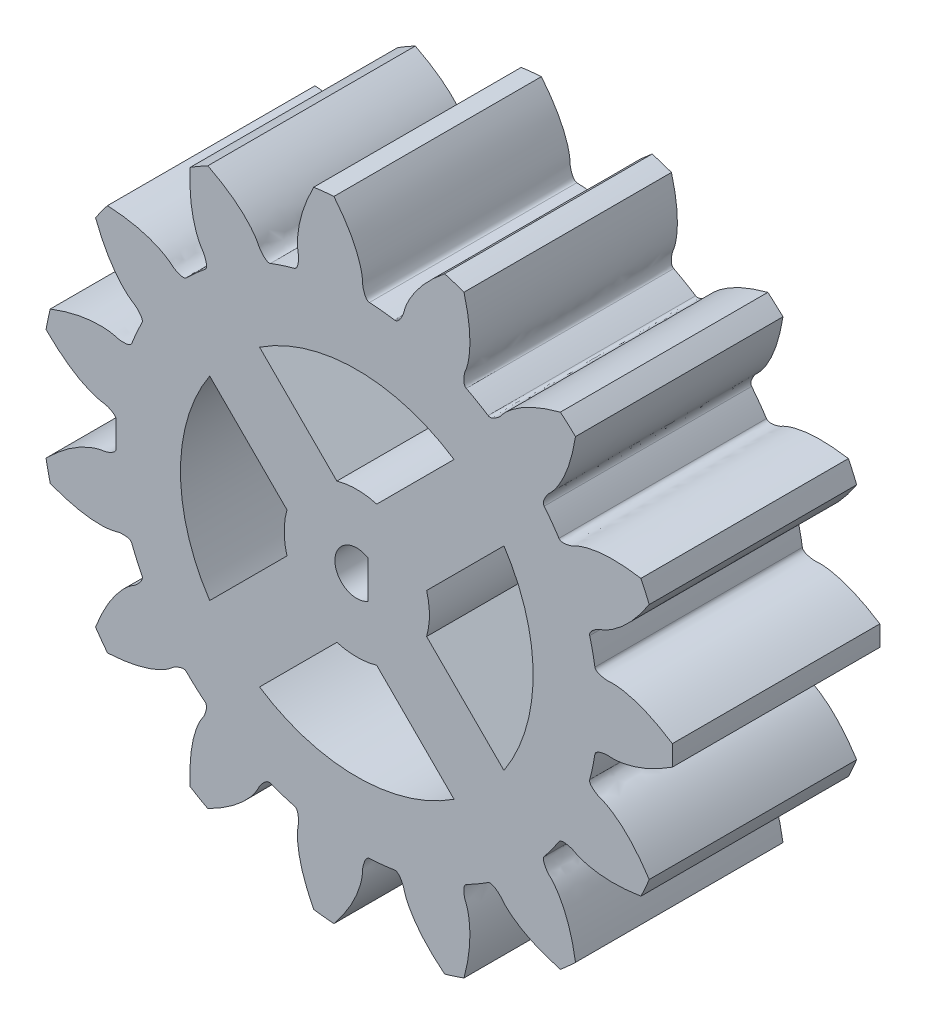
SolidWorks part; units mm, degrees
ref_plane "Front Plane" through (0, 0, 0) normal (0, 0, 1) x (1, 0, 0)
ref_plane "Top Plane" through (0, 0, 0) normal (0, 1, 0) x (1, 0, 0)
ref_plane "Right Plane" through (0, 0, 0) normal (1, 0, 0) x (0, 0, -1)
sketch "Model" plane through (0, 0, 0) normal (0, 0, 1) x (1, 0, 0)
  line L0 (451.3212, 9.2467) -> (451.0258, 8.0362)
  line L1 (451.0258, 8.0362) -> (450.8033, 6.8101)
  line L2 (450.8033, 6.8101) -> (450.8481, 6.7622)
  line L3 (450.8481, 6.7622) -> (451.5704, 6.0588)
  line L4 (451.5704, 6.0588) -> (452.2736, 5.4349)
  line L5 (452.2736, 5.4349) -> (452.9522, 4.8871)
  line L6 (452.9522, 4.8871) -> (453.6007, 4.4118)
  line L7 (453.6007, 4.4118) -> (454.2138, 4.0048)
  line L8 (454.2138, 4.0048) -> (454.7869, 3.6617)
  line L9 (454.7869, 3.6617) -> (455.3153, 3.3779)
  line L10 (455.3153, 3.3779) -> (455.7949, 3.1483)
  line L11 (455.7949, 3.1483) -> (456.222, 2.9678)
  line L12 (456.222, 2.9678) -> (456.5932, 2.8309)
  line L13 (456.5932, 2.8309) -> (456.9055, 2.732)
  line L14 (456.9055, 2.732) -> (457.1563, 2.6652)
  line L15 (457.1563, 2.6652) -> (457.3434, 2.6246)
  line L16 (457.3434, 2.6246) -> (457.9089, 2.5292)
  line L17 (457.9089, 2.5292) -> (458.3538, 2.4053)
  line L18 (458.3538, 2.4053) -> (458.7196, 2.2489)
  line L19 (458.7196, 2.2489) -> (459.0044, 2.0671)
  line L20 (459.0044, 2.0671) -> (459.2067, 1.8671)
  line L21 (459.2067, 1.8671) -> (459.3257, 1.6561)
  line L22 (459.3257, 1.6561) -> (459.3608, 1.4416)
  line L23 (459.3608, 1.4416) -> (459.3257, 0.6868)
  line L24 (459.3257, 0.6868) -> (459.3257, -0.6868)
  line L25 (459.3257, -0.6868) -> (459.3608, -1.4416)
  line L26 (459.3608, -1.4416) -> (459.3257, -1.6561)
  line L27 (459.3257, -1.6561) -> (459.2067, -1.8671)
  line L28 (459.2067, -1.8671) -> (459.0044, -2.0671)
  line L29 (459.0044, -2.0671) -> (458.7196, -2.2489)
  line L30 (458.7196, -2.2489) -> (458.3538, -2.4053)
  line L31 (458.3538, -2.4053) -> (457.9089, -2.5292)
  line L32 (457.9089, -2.5292) -> (457.3434, -2.6246)
  line L33 (457.3434, -2.6246) -> (457.1563, -2.6652)
  line L34 (457.1563, -2.6652) -> (456.9055, -2.732)
  line L35 (456.9055, -2.732) -> (456.5932, -2.8309)
  line L36 (456.5932, -2.8309) -> (456.222, -2.9678)
  line L37 (456.222, -2.9678) -> (455.7949, -3.1483)
  line L38 (455.7949, -3.1483) -> (455.3153, -3.3779)
  line L39 (455.3153, -3.3779) -> (454.7869, -3.6617)
  line L40 (454.7869, -3.6617) -> (454.2138, -4.0048)
  line L41 (454.2138, -4.0048) -> (453.6007, -4.4118)
  line L42 (453.6007, -4.4118) -> (452.9522, -4.8871)
  line L43 (452.9522, -4.8871) -> (452.2736, -5.4349)
  line L44 (452.2736, -5.4349) -> (451.5704, -6.0588)
  line L45 (451.5704, -6.0588) -> (450.8481, -6.7622)
  line L46 (450.8481, -6.7622) -> (450.8033, -6.8101)
  line L47 (450.8033, -6.8101) -> (451.0258, -8.0362)
  line L48 (451.0258, -8.0362) -> (451.3212, -9.2467)
  line L49 (451.3212, -9.2467) -> (451.3817, -9.2723)
  line L50 (451.3817, -9.2723) -> (452.3276, -9.6211)
  line L51 (452.3276, -9.6211) -> (453.2238, -9.905)
  line L52 (453.2238, -9.905) -> (454.0665, -10.1294)
  line L53 (454.0665, -10.1294) -> (454.8522, -10.2999)
  line L54 (454.8522, -10.2999) -> (455.5779, -10.4224)
  line L55 (455.5779, -10.4224) -> (456.2409, -10.5027)
  line L56 (456.2409, -10.5027) -> (456.8391, -10.5471)
  line L57 (456.8391, -10.5471) -> (457.3707, -10.5617)
  line L58 (457.3707, -10.5617) -> (457.8343, -10.5529)
  line L59 (457.8343, -10.5529) -> (458.2291, -10.527)
  line L60 (458.2291, -10.527) -> (458.5546, -10.4903)
  line L61 (458.5546, -10.4903) -> (458.8109, -10.4493)
  line L62 (458.8109, -10.4493) -> (458.9983, -10.4103)
  line L63 (458.9983, -10.4103) -> (459.5537, -10.2675)
  line L64 (459.5537, -10.2675) -> (460.0105, -10.1996)
  line L65 (460.0105, -10.1996) -> (460.4084, -10.1937)
  line L66 (460.4084, -10.1937) -> (460.7425, -10.244)
  line L67 (460.7425, -10.244) -> (461.0087, -10.3444)
  line L68 (461.0087, -10.3444) -> (461.2031, -10.4888)
  line L69 (461.2031, -10.4888) -> (461.3225, -10.6705)
  line L70 (461.3225, -10.6705) -> (461.5974, -11.3743)
  line L71 (461.5974, -11.3743) -> (462.1561, -12.6291)
  line L72 (462.1561, -12.6291) -> (462.4952, -13.3044)
  line L73 (462.4952, -13.3044) -> (462.5503, -13.5147)
  line L74 (462.5503, -13.5147) -> (462.5275, -13.7558)
  line L75 (462.5275, -13.7558) -> (462.424, -14.0208)
  line L76 (462.424, -14.0208) -> (462.2378, -14.3027)
  line L77 (462.2378, -14.3027) -> (461.9672, -14.5944)
  line L78 (461.9672, -14.5944) -> (461.6111, -14.8885)
  line L79 (461.6111, -14.8885) -> (461.1333, -15.2057)
  line L80 (461.1333, -15.2057) -> (460.9789, -15.3189)
  line L81 (460.9789, -15.3189) -> (460.777, -15.4819)
  line L82 (460.777, -15.4819) -> (460.5319, -15.6993)
  line L83 (460.5319, -15.6993) -> (460.2485, -15.9753)
  line L84 (460.2485, -15.9753) -> (459.9317, -16.3139)
  line L85 (459.9317, -16.3139) -> (459.5869, -16.7187)
  line L86 (459.5869, -16.7187) -> (459.2196, -17.193)
  line L87 (459.2196, -17.193) -> (458.8357, -17.7395)
  line L88 (458.8357, -17.7395) -> (458.4411, -18.3607)
  line L89 (458.4411, -18.3607) -> (458.0421, -19.0587)
  line L90 (458.0421, -19.0587) -> (457.6449, -19.8351)
  line L91 (457.6449, -19.8351) -> (457.2562, -20.6911)
  line L92 (457.2562, -20.6911) -> (456.8825, -21.6274)
  line L93 (456.8825, -21.6274) -> (456.861, -21.6895)
  line L94 (456.861, -21.6895) -> (457.563, -22.719)
  line L95 (457.563, -22.719) -> (458.3252, -23.7048)
  line L96 (458.3252, -23.7048) -> (458.3909, -23.7035)
  line L97 (458.3909, -23.7035) -> (459.3969, -23.6375)
  line L98 (459.3969, -23.6375) -> (460.3311, -23.5323)
  line L99 (460.3311, -23.5323) -> (461.1922, -23.3945)
  line L100 (461.1922, -23.3945) -> (461.9794, -23.2307)
  line L101 (461.9794, -23.2307) -> (462.6921, -23.0474)
  line L102 (462.6921, -23.0474) -> (463.3305, -22.8511)
  line L103 (463.3305, -22.8511) -> (463.895, -22.6483)
  line L104 (463.895, -22.6483) -> (464.3866, -22.4455)
  line L105 (464.3866, -22.4455) -> (464.8065, -22.2489)
  line L106 (464.8065, -22.2489) -> (465.1566, -22.0646)
  line L107 (465.1566, -22.0646) -> (465.4391, -21.8987)
  line L108 (465.4391, -21.8987) -> (465.6565, -21.757)
  line L109 (465.6565, -21.757) -> (465.8119, -21.6452)
  line L110 (465.8119, -21.6452) -> (466.2612, -21.2888)
  line L111 (466.2612, -21.2888) -> (466.6509, -21.041)
  line L112 (466.6509, -21.041) -> (467.012, -20.8738)
  line L113 (467.012, -20.8738) -> (467.3376, -20.7838)
  line L114 (467.3376, -20.7838) -> (467.6217, -20.7673)
  line L115 (467.6217, -20.7673) -> (467.858, -20.8201)
  line L116 (467.858, -20.8201) -> (468.041, -20.9375)
  line L117 (468.041, -20.9375) -> (468.5784, -21.4687)
  line L118 (468.5784, -21.4687) -> (469.5992, -22.3878)
  line L119 (469.5992, -22.3878) -> (470.1836, -22.8667)
  line L120 (470.1836, -22.8667) -> (470.3195, -23.0364)
  line L121 (470.3195, -23.0364) -> (470.3967, -23.2659)
  line L122 (470.3967, -23.2659) -> (470.41, -23.5501)
  line L123 (470.41, -23.5501) -> (470.3545, -23.8834)
  line L124 (470.3545, -23.8834) -> (470.226, -24.26)
  line L125 (470.226, -24.26) -> (470.0203, -24.6735)
  line L126 (470.0203, -24.6735) -> (469.7128, -25.1576)
  line L127 (469.7128, -25.1576) -> (469.6178, -25.3238)
  line L128 (469.6178, -25.3238) -> (469.4996, -25.5548)
  line L129 (469.4996, -25.5548) -> (469.3642, -25.8531)
  line L130 (469.3642, -25.8531) -> (469.2175, -26.2205)
  line L131 (469.2175, -26.2205) -> (469.0659, -26.6587)
  line L132 (469.0659, -26.6587) -> (468.9155, -27.1688)
  line L133 (468.9155, -27.1688) -> (468.7729, -27.7514)
  line L134 (468.7729, -27.7514) -> (468.6444, -28.4068)
  line L135 (468.6444, -28.4068) -> (468.5366, -29.1348)
  line L136 (468.5366, -29.1348) -> (468.4559, -29.9348)
  line L137 (468.4559, -29.9348) -> (468.4089, -30.8056)
  line L138 (468.4089, -30.8056) -> (468.402, -31.7457)
  line L139 (468.402, -31.7457) -> (468.4414, -32.7531)
  line L140 (468.4414, -32.7531) -> (468.4471, -32.8185)
  line L141 (468.4471, -32.8185) -> (469.5071, -33.4735)
  line L142 (469.5071, -33.4735) -> (470.6044, -34.064)
  line L143 (470.6044, -34.064) -> (470.6638, -34.0362)
  line L144 (470.6638, -34.0362) -> (471.556, -33.5666)
  line L145 (471.556, -33.5666) -> (472.3667, -33.0906)
  line L146 (472.3667, -33.0906) -> (473.0973, -32.6145)
  line L147 (473.0973, -32.6145) -> (473.7498, -32.1447)
  line L148 (473.7498, -32.1447) -> (474.3263, -31.6873)
  line L149 (474.3263, -31.6873) -> (474.8297, -31.2483)
  line L150 (474.8297, -31.2483) -> (475.2629, -30.8335)
  line L151 (475.2629, -30.8335) -> (475.6295, -30.4483)
  line L152 (475.6295, -30.4483) -> (475.9332, -30.0978)
  line L153 (475.9332, -30.0978) -> (476.1781, -29.7871)
  line L154 (476.1781, -29.7871) -> (476.3686, -29.5207)
  line L155 (476.3686, -29.5207) -> (476.5096, -29.3028)
  line L156 (476.5096, -29.3028) -> (476.6061, -29.1374)
  line L157 (476.6061, -29.1374) -> (476.8715, -28.6291)
  line L158 (476.8715, -28.6291) -> (477.1268, -28.2442)
  line L159 (477.1268, -28.2442) -> (477.3886, -27.9446)
  line L160 (477.3886, -27.9446) -> (477.6496, -27.7299)
  line L161 (477.6496, -27.7299) -> (477.9023, -27.5993)
  line L162 (477.9023, -27.5993) -> (478.1397, -27.5514)
  line L163 (478.1397, -27.5514) -> (478.3546, -27.5842)
  line L164 (478.3546, -27.5842) -> (479.0616, -27.8509)
  line L165 (479.0616, -27.8509) -> (480.3679, -28.2754)
  line L166 (480.3679, -28.2754) -> (481.0967, -28.4752)
  line L167 (481.0967, -28.4752) -> (481.2898, -28.5749)
  line L168 (481.2898, -28.5749) -> (481.4537, -28.7532)
  line L169 (481.4537, -28.7532) -> (481.5814, -29.0075)
  line L170 (481.5814, -29.0075) -> (481.6663, -29.3345)
  line L171 (481.6663, -29.3345) -> (481.7021, -29.7308)
  line L172 (481.7021, -29.7308) -> (481.6823, -30.1922)
  line L173 (481.6823, -30.1922) -> (481.5983, -30.7595)
  line L174 (481.5983, -30.7595) -> (481.5791, -30.95)
  line L175 (481.5791, -30.95) -> (481.5651, -31.2091)
  line L176 (481.5651, -31.2091) -> (481.5627, -31.5367)
  line L177 (481.5627, -31.5367) -> (481.5782, -31.932)
  line L178 (481.5782, -31.932) -> (481.6179, -32.394)
  line L179 (481.6179, -32.394) -> (481.688, -32.9211)
  line L180 (481.688, -32.9211) -> (481.7947, -33.5114)
  line L181 (481.7947, -33.5114) -> (481.9439, -34.1624)
  line L182 (481.9439, -34.1624) -> (482.1415, -34.8713)
  line L183 (482.1415, -34.8713) -> (482.3932, -35.6349)
  line L184 (482.3932, -35.6349) -> (482.7044, -36.4495)
  line L185 (482.7044, -36.4495) -> (483.0805, -37.3112)
  line L186 (483.0805, -37.3112) -> (483.5263, -38.2154)
  line L187 (483.5263, -38.2154) -> (483.558, -38.2729)
  line L188 (483.558, -38.2729) -> (484.7928, -38.4402)
  line L189 (484.7928, -38.4402) -> (486.0354, -38.5333)
  line L190 (486.0354, -38.5333) -> (486.0784, -38.4837)
  line L191 (486.0784, -38.4837) -> (486.7025, -37.6919)
  line L192 (486.7025, -37.6919) -> (487.2494, -36.9272)
  line L193 (487.2494, -36.9272) -> (487.7232, -36.1951)
  line L194 (487.7232, -36.1951) -> (488.1282, -35.5005)
  line L195 (488.1282, -35.5005) -> (488.4689, -34.8482)
  line L196 (488.4689, -34.8482) -> (488.7502, -34.2424)
  line L197 (488.7502, -34.2424) -> (488.9772, -33.6872)
  line L198 (488.9772, -33.6872) -> (489.1554, -33.1862)
  line L199 (489.1554, -33.1862) -> (489.2903, -32.7426)
  line L200 (489.2903, -32.7426) -> (489.3876, -32.3591)
  line L201 (489.3876, -32.3591) -> (489.4534, -32.0382)
  line L202 (489.4534, -32.0382) -> (489.4936, -31.7818)
  line L203 (489.4936, -31.7818) -> (489.5144, -31.5915)
  line L204 (489.5144, -31.5915) -> (489.5502, -31.0192)
  line L205 (489.5502, -31.0192) -> (489.6268, -30.5637)
  line L206 (489.6268, -30.5637) -> (489.7441, -30.1835)
  line L207 (489.7441, -30.1835) -> (489.8952, -29.8813)
  line L208 (489.8952, -29.8813) -> (490.073, -29.6592)
  line L209 (490.073, -29.6592) -> (490.2704, -29.5188)
  line L210 (490.2704, -29.5188) -> (490.48, -29.4614)
  line L211 (490.48, -29.4614) -> (491.2344, -29.4175)
  line L212 (491.2344, -29.4175) -> (492.6004, -29.2739)
  line L213 (492.6004, -29.2739) -> (493.3474, -29.1601)
  line L214 (493.3474, -29.1601) -> (493.5644, -29.1726)
  line L215 (493.5644, -29.1726) -> (493.7867, -29.2688)
  line L216 (493.7867, -29.2688) -> (494.0068, -29.4491)
  line L217 (494.0068, -29.4491) -> (494.2174, -29.7134)
  line L218 (494.2174, -29.7134) -> (494.4111, -30.0608)
  line L219 (494.4111, -30.0608) -> (494.5808, -30.4904)
  line L220 (494.5808, -30.4904) -> (494.7348, -31.0428)
  line L221 (494.7348, -31.0428) -> (494.7948, -31.2246)
  line L222 (494.7948, -31.2246) -> (494.8874, -31.4671)
  line L223 (494.8874, -31.4671) -> (495.0184, -31.7673)
  line L224 (495.0184, -31.7673) -> (495.1933, -32.1221)
  line L225 (495.1933, -32.1221) -> (495.4175, -32.5281)
  line L226 (495.4175, -32.5281) -> (495.696, -32.9811)
  line L227 (495.696, -32.9811) -> (496.0335, -33.4769)
  line L228 (496.0335, -33.4769) -> (496.4346, -34.011)
  line L229 (496.4346, -34.011) -> (496.9035, -34.5782)
  line L230 (496.9035, -34.5782) -> (497.444, -35.1734)
  line L231 (497.444, -35.1734) -> (498.0596, -35.791)
  line L232 (498.0596, -35.791) -> (498.7536, -36.4252)
  line L233 (498.7536, -36.4252) -> (499.5287, -37.07)
  line L234 (499.5287, -37.07) -> (499.581, -37.1096)
  line L235 (499.581, -37.1096) -> (500.7771, -36.7602)
  line L236 (500.7771, -36.7602) -> (501.9502, -36.3398)
  line L237 (501.9502, -36.3398) -> (501.9693, -36.277)
  line L238 (501.9693, -36.277) -> (502.2173, -35.2998)
  line L239 (502.2173, -35.2998) -> (502.406, -34.3788)
  line L240 (502.406, -34.3788) -> (502.5411, -33.5173)
  line L241 (502.5411, -33.5173) -> (502.6285, -32.718)
  line L242 (502.6285, -32.718) -> (502.6744, -31.9835)
  line L243 (502.6744, -31.9835) -> (502.685, -31.3157)
  line L244 (502.685, -31.3157) -> (502.6666, -30.7162)
  line L245 (502.6666, -30.7162) -> (502.6256, -30.186)
  line L246 (502.6256, -30.186) -> (502.5684, -29.7258)
  line L247 (502.5684, -29.7258) -> (502.5013, -29.3359)
  line L248 (502.5013, -29.3359) -> (502.4308, -29.016)
  line L249 (502.4308, -29.016) -> (502.3633, -28.7655)
  line L250 (502.3633, -28.7655) -> (502.3049, -28.5831)
  line L251 (502.3049, -28.5831) -> (502.1048, -28.0457)
  line L252 (502.1048, -28.0457) -> (501.9896, -27.5984)
  line L253 (501.9896, -27.5984) -> (501.9421, -27.2034)
  line L254 (501.9421, -27.2034) -> (501.9572, -26.8659)
  line L255 (501.9572, -26.8659) -> (502.0293, -26.5907)
  line L256 (502.0293, -26.5907) -> (502.1525, -26.3822)
  line L257 (502.1525, -26.3822) -> (502.3207, -26.2445)
  line L258 (502.3207, -26.2445) -> (502.9919, -25.8975)
  line L259 (502.9919, -25.8975) -> (504.1815, -25.2107)
  line L260 (504.1815, -25.2107) -> (504.8176, -24.8029)
  line L261 (504.8176, -24.8029) -> (505.021, -24.7261)
  line L262 (505.021, -24.7261) -> (505.2631, -24.7236)
  line L263 (505.2631, -24.7236) -> (505.5375, -24.7988)
  line L264 (505.5375, -24.7988) -> (505.8374, -24.9545)
  line L265 (505.8374, -24.9545) -> (506.1557, -25.1931)
  line L266 (506.1557, -25.1931) -> (506.4855, -25.5165)
  line L267 (506.4855, -25.5165) -> (506.8508, -25.9585)
  line L268 (506.8508, -25.9585) -> (506.9795, -26.1003)
  line L269 (506.9795, -26.1003) -> (507.1628, -26.2841)
  line L270 (507.1628, -26.2841) -> (507.4046, -26.505)
  line L271 (507.4046, -26.505) -> (507.7087, -26.7581)
  line L272 (507.7087, -26.7581) -> (508.0786, -27.0377)
  line L273 (508.0786, -27.0377) -> (508.5172, -27.3383)
  line L274 (508.5172, -27.3383) -> (509.0273, -27.654)
  line L275 (509.0273, -27.654) -> (509.6109, -27.9787)
  line L276 (509.6109, -27.9787) -> (510.27, -28.3062)
  line L277 (510.27, -28.3062) -> (511.0058, -28.6301)
  line L278 (511.0058, -28.6301) -> (511.8195, -28.9439)
  line L279 (511.8195, -28.9439) -> (512.7114, -29.241)
  line L280 (512.7114, -29.241) -> (513.6817, -29.5148)
  line L281 (513.6817, -29.5148) -> (513.7457, -29.5297)
  line L282 (513.7457, -29.5297) -> (514.6962, -28.724)
  line L283 (514.6962, -28.724) -> (515.5969, -27.8628)
  line L284 (515.5969, -27.8628) -> (515.5888, -27.7977)
  line L285 (515.5888, -27.7977) -> (515.4179, -26.8041)
  line L286 (515.4179, -26.8041) -> (515.2157, -25.886)
  line L287 (515.2157, -25.886) -> (514.9886, -25.044)
  line L288 (514.9886, -25.044) -> (514.7434, -24.2783)
  line L289 (514.7434, -24.2783) -> (514.4866, -23.5886)
  line L290 (514.4866, -23.5886) -> (514.2247, -22.9742)
  line L291 (514.2247, -22.9742) -> (513.964, -22.434)
  line L292 (513.964, -22.434) -> (513.7109, -21.9663)
  line L293 (513.7109, -21.9663) -> (513.4715, -21.5693)
  line L294 (513.4715, -21.5693) -> (513.2516, -21.2403)
  line L295 (513.2516, -21.2403) -> (513.0571, -20.9767)
  line L296 (513.0571, -20.9767) -> (512.8935, -20.7753)
  line L297 (512.8935, -20.7753) -> (512.766, -20.6325)
  line L298 (512.766, -20.6325) -> (512.3646, -20.2229)
  line L299 (512.3646, -20.2229) -> (512.0774, -19.8612)
  line L300 (512.0774, -19.8612) -> (511.8734, -19.5196)
  line L301 (511.8734, -19.5196) -> (511.7499, -19.2051)
  line L302 (511.7499, -19.2051) -> (511.7038, -18.9244)
  line L303 (511.7038, -18.9244) -> (511.7315, -18.6838)
  line L304 (511.7315, -18.6838) -> (511.8292, -18.4896)
  line L305 (511.8292, -18.4896) -> (512.3013, -17.8996)
  line L306 (512.3013, -17.8996) -> (513.1087, -16.7884)
  line L307 (513.1087, -16.7884) -> (513.5239, -16.1571)
  line L308 (513.5239, -16.1571) -> (513.6784, -16.0042)
  line L309 (513.6784, -16.0042) -> (513.8987, -15.9034)
  line L310 (513.8987, -15.9034) -> (514.1799, -15.8605)
  line L311 (514.1799, -15.8605) -> (514.5172, -15.8808)
  line L312 (514.5172, -15.8808) -> (514.9051, -15.9693)
  line L313 (514.9051, -15.9693) -> (515.3379, -16.1306)
  line L314 (515.3379, -16.1306) -> (515.8514, -16.3858)
  line L315 (515.8514, -16.3858) -> (516.0266, -16.4629)
  line L316 (516.0266, -16.4629) -> (516.2688, -16.5563)
  line L317 (516.2688, -16.5563) -> (516.5795, -16.6598)
  line L318 (516.5795, -16.6598) -> (516.9603, -16.7673)
  line L319 (516.9603, -16.7673) -> (517.412, -16.8723)
  line L320 (517.412, -16.8723) -> (517.9349, -16.9685)
  line L321 (517.9349, -16.9685) -> (518.5293, -17.0495)
  line L322 (518.5293, -17.0495) -> (519.1945, -17.1087)
  line L323 (519.1945, -17.1087) -> (519.9298, -17.1398)
  line L324 (519.9298, -17.1398) -> (520.7338, -17.1364)
  line L325 (520.7338, -17.1364) -> (521.6048, -17.0922)
  line L326 (521.6048, -17.0922) -> (522.5404, -17.0008)
  line L327 (522.5404, -17.0008) -> (523.5382, -16.8563)
  line L328 (523.5382, -16.8563) -> (523.6027, -16.8438)
  line L329 (523.6027, -16.8438) -> (524.1433, -15.7212)
  line L330 (524.1433, -15.7212) -> (524.6159, -14.5681)
  line L331 (524.6159, -14.5681) -> (524.582, -14.5119)
  line L332 (524.582, -14.5119) -> (524.0217, -13.6737)
  line L333 (524.0217, -13.6737) -> (523.4635, -12.9172)
  line L334 (523.4635, -12.9172) -> (522.9137, -12.2404)
  line L335 (522.9137, -12.2404) -> (522.3782, -11.6406)
  line L336 (522.3782, -11.6406) -> (521.8631, -11.115)
  line L337 (521.8631, -11.115) -> (521.3739, -10.6603)
  line L338 (521.3739, -10.6603) -> (520.9161, -10.2728)
  line L339 (520.9161, -10.2728) -> (520.4946, -9.9485)
  line L340 (520.4946, -9.9485) -> (520.1144, -9.6831)
  line L341 (520.1144, -9.6831) -> (519.7798, -9.4721)
  line L342 (519.7798, -9.4721) -> (519.4949, -9.3104)
  line L343 (519.4949, -9.3104) -> (519.2634, -9.1929)
  line L344 (519.2634, -9.1929) -> (519.0889, -9.1143)
  line L345 (519.0889, -9.1143) -> (518.5556, -8.9034)
  line L346 (518.5556, -8.9034) -> (518.1461, -8.6898)
  line L347 (518.1461, -8.6898) -> (517.8208, -8.4607)
  line L348 (517.8208, -8.4607) -> (517.5801, -8.2237)
  line L349 (517.5801, -8.2237) -> (517.4237, -7.9859)
  line L350 (517.4237, -7.9859) -> (517.3513, -7.7548)
  line L351 (517.3513, -7.7548) -> (517.3615, -7.5377)
  line L352 (517.3615, -7.5377) -> (517.5528, -6.8067)
  line L353 (517.5528, -6.8067) -> (517.8384, -5.4631)
  line L354 (517.8384, -5.4631) -> (517.9609, -4.7175)
  line L355 (517.9609, -4.7175) -> (518.0399, -4.515)
  line L356 (518.0399, -4.515) -> (518.2001, -4.3334)
  line L357 (518.2001, -4.3334) -> (518.4396, -4.1798)
  line L358 (518.4396, -4.1798) -> (518.756, -4.0611)
  line L359 (518.756, -4.0611) -> (519.1463, -3.9842)
  line L360 (519.1463, -3.9842) -> (519.6073, -3.9556)
  line L361 (519.6073, -3.9556) -> (520.1802, -3.9798)
  line L362 (520.1802, -3.9798) -> (520.3717, -3.979)
  line L363 (520.3717, -3.979) -> (520.6309, -3.9658)
  line L364 (520.6309, -3.9658) -> (520.9569, -3.934)
  line L365 (520.9569, -3.934) -> (521.3485, -3.8773)
  line L366 (521.3485, -3.8773) -> (521.8038, -3.7895)
  line L367 (521.8038, -3.7895) -> (522.3207, -3.6647)
  line L368 (522.3207, -3.6647) -> (522.8965, -3.4969)
  line L369 (522.8965, -3.4969) -> (523.5284, -3.2805)
  line L370 (523.5284, -3.2805) -> (524.2128, -3.0098)
  line L371 (524.2128, -3.0098) -> (524.9459, -2.6797)
  line L372 (524.9459, -2.6797) -> (525.7235, -2.285)
  line L373 (525.7235, -2.285) -> (526.5411, -1.821)
  line L374 (526.5411, -1.821) -> (527.3938, -1.2831)
  line L375 (527.3938, -1.2831) -> (527.4477, -1.2455)
  line L376 (527.4477, -1.2455) -> (527.485, 0)
  line L377 (527.485, 0) -> (527.4477, 1.2455)
  line L378 (527.4477, 1.2455) -> (527.3938, 1.2831)
  line L379 (527.3938, 1.2831) -> (526.5411, 1.821)
  line L380 (526.5411, 1.821) -> (525.7235, 2.285)
  line L381 (525.7235, 2.285) -> (524.9459, 2.6797)
  line L382 (524.9459, 2.6797) -> (524.2128, 3.0098)
  line L383 (524.2128, 3.0098) -> (523.5284, 3.2805)
  line L384 (523.5284, 3.2805) -> (522.8965, 3.4969)
  line L385 (522.8965, 3.4969) -> (522.3207, 3.6647)
  line L386 (522.3207, 3.6647) -> (521.8038, 3.7895)
  line L387 (521.8038, 3.7895) -> (521.3485, 3.8773)
  line L388 (521.3485, 3.8773) -> (520.9569, 3.934)
  line L389 (520.9569, 3.934) -> (520.6309, 3.9658)
  line L390 (520.6309, 3.9658) -> (520.3717, 3.979)
  line L391 (520.3717, 3.979) -> (520.1802, 3.9798)
  line L392 (520.1802, 3.9798) -> (519.6073, 3.9556)
  line L393 (519.6073, 3.9556) -> (519.1463, 3.9842)
  line L394 (519.1463, 3.9842) -> (518.756, 4.0611)
  line L395 (518.756, 4.0611) -> (518.4396, 4.1798)
  line L396 (518.4396, 4.1798) -> (518.2001, 4.3334)
  line L397 (518.2001, 4.3334) -> (518.0399, 4.515)
  line L398 (518.0399, 4.515) -> (517.9609, 4.7175)
  line L399 (517.9609, 4.7175) -> (517.8384, 5.4631)
  line L400 (517.8384, 5.4631) -> (517.5528, 6.8067)
  line L401 (517.5528, 6.8067) -> (517.3615, 7.5377)
  line L402 (517.3615, 7.5377) -> (517.3513, 7.7548)
  line L403 (517.3513, 7.7548) -> (517.4237, 7.9859)
  line L404 (517.4237, 7.9859) -> (517.5801, 8.2237)
  line L405 (517.5801, 8.2237) -> (517.8208, 8.4607)
  line L406 (517.8208, 8.4607) -> (518.1461, 8.6898)
  line L407 (518.1461, 8.6898) -> (518.5556, 8.9034)
  line L408 (518.5556, 8.9034) -> (519.0889, 9.1143)
  line L409 (519.0889, 9.1143) -> (519.2634, 9.1929)
  line L410 (519.2634, 9.1929) -> (519.4949, 9.3104)
  line L411 (519.4949, 9.3104) -> (519.7798, 9.4721)
  line L412 (519.7798, 9.4721) -> (520.1144, 9.6831)
  line L413 (520.1144, 9.6831) -> (520.4946, 9.9485)
  line L414 (520.4946, 9.9485) -> (520.9161, 10.2728)
  line L415 (520.9161, 10.2728) -> (521.3739, 10.6603)
  line L416 (521.3739, 10.6603) -> (521.8631, 11.115)
  line L417 (521.8631, 11.115) -> (522.3782, 11.6406)
  line L418 (522.3782, 11.6406) -> (522.9137, 12.2404)
  line L419 (522.9137, 12.2404) -> (523.4635, 12.9172)
  line L420 (523.4635, 12.9172) -> (524.0217, 13.6737)
  line L421 (524.0217, 13.6737) -> (524.582, 14.5119)
  line L422 (524.582, 14.5119) -> (524.6159, 14.5681)
  line L423 (524.6159, 14.5681) -> (524.1433, 15.7212)
  line L424 (524.1433, 15.7212) -> (523.6027, 16.8438)
  line L425 (523.6027, 16.8438) -> (523.5382, 16.8563)
  line L426 (523.5382, 16.8563) -> (522.5404, 17.0008)
  line L427 (522.5404, 17.0008) -> (521.6048, 17.0922)
  line L428 (521.6048, 17.0922) -> (520.7338, 17.1364)
  line L429 (520.7338, 17.1364) -> (519.9298, 17.1398)
  line L430 (519.9298, 17.1398) -> (519.1945, 17.1087)
  line L431 (519.1945, 17.1087) -> (518.5293, 17.0495)
  line L432 (518.5293, 17.0495) -> (517.9349, 16.9685)
  line L433 (517.9349, 16.9685) -> (517.412, 16.8723)
  line L434 (517.412, 16.8723) -> (516.9603, 16.7673)
  line L435 (516.9603, 16.7673) -> (516.5795, 16.6598)
  line L436 (516.5795, 16.6598) -> (516.2688, 16.5563)
  line L437 (516.2688, 16.5563) -> (516.0266, 16.4629)
  line L438 (516.0266, 16.4629) -> (515.8514, 16.3858)
  line L439 (515.8514, 16.3858) -> (515.3379, 16.1306)
  line L440 (515.3379, 16.1306) -> (514.9051, 15.9693)
  line L441 (514.9051, 15.9693) -> (514.5172, 15.8808)
  line L442 (514.5172, 15.8808) -> (514.1799, 15.8605)
  line L443 (514.1799, 15.8605) -> (513.8987, 15.9034)
  line L444 (513.8987, 15.9034) -> (513.6784, 16.0042)
  line L445 (513.6784, 16.0042) -> (513.5239, 16.1571)
  line L446 (513.5239, 16.1571) -> (513.1087, 16.7884)
  line L447 (513.1087, 16.7884) -> (512.3013, 17.8996)
  line L448 (512.3013, 17.8996) -> (511.8292, 18.4896)
  line L449 (511.8292, 18.4896) -> (511.7315, 18.6838)
  line L450 (511.7315, 18.6838) -> (511.7038, 18.9244)
  line L451 (511.7038, 18.9244) -> (511.7499, 19.2051)
  line L452 (511.7499, 19.2051) -> (511.8734, 19.5196)
  line L453 (511.8734, 19.5196) -> (512.0774, 19.8612)
  line L454 (512.0774, 19.8612) -> (512.3646, 20.2229)
  line L455 (512.3646, 20.2229) -> (512.766, 20.6325)
  line L456 (512.766, 20.6325) -> (512.8935, 20.7753)
  line L457 (512.8935, 20.7753) -> (513.0571, 20.9767)
  line L458 (513.0571, 20.9767) -> (513.2516, 21.2403)
  line L459 (513.2516, 21.2403) -> (513.4715, 21.5693)
  line L460 (513.4715, 21.5693) -> (513.7109, 21.9663)
  line L461 (513.7109, 21.9663) -> (513.964, 22.434)
  line L462 (513.964, 22.434) -> (514.2247, 22.9742)
  line L463 (514.2247, 22.9742) -> (514.4866, 23.5886)
  line L464 (514.4866, 23.5886) -> (514.7434, 24.2783)
  line L465 (514.7434, 24.2783) -> (514.9886, 25.044)
  line L466 (514.9886, 25.044) -> (515.2157, 25.886)
  line L467 (515.2157, 25.886) -> (515.4179, 26.8041)
  line L468 (515.4179, 26.8041) -> (515.5888, 27.7977)
  line L469 (515.5888, 27.7977) -> (515.5969, 27.8628)
  line L470 (515.5969, 27.8628) -> (514.6962, 28.724)
  line L471 (514.6962, 28.724) -> (513.7457, 29.5297)
  line L472 (513.7457, 29.5297) -> (513.6817, 29.5148)
  line L473 (513.6817, 29.5148) -> (512.7114, 29.241)
  line L474 (512.7114, 29.241) -> (511.8195, 28.9439)
  line L475 (511.8195, 28.9439) -> (511.0058, 28.6301)
  line L476 (511.0058, 28.6301) -> (510.27, 28.3062)
  line L477 (510.27, 28.3062) -> (509.6109, 27.9787)
  line L478 (509.6109, 27.9787) -> (509.0273, 27.654)
  line L479 (509.0273, 27.654) -> (508.5172, 27.3383)
  line L480 (508.5172, 27.3383) -> (508.0786, 27.0377)
  line L481 (508.0786, 27.0377) -> (507.7087, 26.7581)
  line L482 (507.7087, 26.7581) -> (507.4046, 26.505)
  line L483 (507.4046, 26.505) -> (507.1628, 26.2841)
  line L484 (507.1628, 26.2841) -> (506.9795, 26.1003)
  line L485 (506.9795, 26.1003) -> (506.8508, 25.9585)
  line L486 (506.8508, 25.9585) -> (506.4855, 25.5165)
  line L487 (506.4855, 25.5165) -> (506.1557, 25.1931)
  line L488 (506.1557, 25.1931) -> (505.8374, 24.9545)
  line L489 (505.8374, 24.9545) -> (505.5375, 24.7988)
  line L490 (505.5375, 24.7988) -> (505.2631, 24.7236)
  line L491 (505.2631, 24.7236) -> (505.021, 24.7261)
  line L492 (505.021, 24.7261) -> (504.8176, 24.8029)
  line L493 (504.8176, 24.8029) -> (504.1815, 25.2107)
  line L494 (504.1815, 25.2107) -> (502.9919, 25.8975)
  line L495 (502.9919, 25.8975) -> (502.3207, 26.2445)
  line L496 (502.3207, 26.2445) -> (502.1525, 26.3822)
  line L497 (502.1525, 26.3822) -> (502.0293, 26.5907)
  line L498 (502.0293, 26.5907) -> (501.9572, 26.8659)
  line L499 (501.9572, 26.8659) -> (501.9421, 27.2034)
  line L500 (501.9421, 27.2034) -> (501.9896, 27.5984)
  line L501 (501.9896, 27.5984) -> (502.1048, 28.0457)
  line L502 (502.1048, 28.0457) -> (502.3049, 28.5831)
  line L503 (502.3049, 28.5831) -> (502.3633, 28.7655)
  line L504 (502.3633, 28.7655) -> (502.4308, 29.016)
  line L505 (502.4308, 29.016) -> (502.5013, 29.3359)
  line L506 (502.5013, 29.3359) -> (502.5684, 29.7258)
  line L507 (502.5684, 29.7258) -> (502.6256, 30.186)
  line L508 (502.6256, 30.186) -> (502.6666, 30.7162)
  line L509 (502.6666, 30.7162) -> (502.685, 31.3157)
  line L510 (502.685, 31.3157) -> (502.6744, 31.9835)
  line L511 (502.6744, 31.9835) -> (502.6285, 32.718)
  line L512 (502.6285, 32.718) -> (502.5411, 33.5173)
  line L513 (502.5411, 33.5173) -> (502.406, 34.3788)
  line L514 (502.406, 34.3788) -> (502.2173, 35.2998)
  line L515 (502.2173, 35.2998) -> (501.9693, 36.277)
  line L516 (501.9693, 36.277) -> (501.9502, 36.3398)
  line L517 (501.9502, 36.3398) -> (500.7771, 36.7602)
  line L518 (500.7771, 36.7602) -> (499.581, 37.1096)
  line L519 (499.581, 37.1096) -> (499.5287, 37.07)
  line L520 (499.5287, 37.07) -> (498.7536, 36.4252)
  line L521 (498.7536, 36.4252) -> (498.0596, 35.791)
  line L522 (498.0596, 35.791) -> (497.444, 35.1734)
  line L523 (497.444, 35.1734) -> (496.9035, 34.5782)
  line L524 (496.9035, 34.5782) -> (496.4346, 34.011)
  line L525 (496.4346, 34.011) -> (496.0335, 33.4769)
  line L526 (496.0335, 33.4769) -> (495.696, 32.9811)
  line L527 (495.696, 32.9811) -> (495.4175, 32.5281)
  line L528 (495.4175, 32.5281) -> (495.1933, 32.1221)
  line L529 (495.1933, 32.1221) -> (495.0184, 31.7673)
  line L530 (495.0184, 31.7673) -> (494.8874, 31.4671)
  line L531 (494.8874, 31.4671) -> (494.7948, 31.2246)
  line L532 (494.7948, 31.2246) -> (494.7348, 31.0428)
  line L533 (494.7348, 31.0428) -> (494.5808, 30.4904)
  line L534 (494.5808, 30.4904) -> (494.4111, 30.0608)
  line L535 (494.4111, 30.0608) -> (494.2174, 29.7134)
  line L536 (494.2174, 29.7134) -> (494.0068, 29.4491)
  line L537 (494.0068, 29.4491) -> (493.7867, 29.2688)
  line L538 (493.7867, 29.2688) -> (493.5644, 29.1726)
  line L539 (493.5644, 29.1726) -> (493.3474, 29.1601)
  line L540 (493.3474, 29.1601) -> (492.6004, 29.2739)
  line L541 (492.6004, 29.2739) -> (491.2344, 29.4175)
  line L542 (491.2344, 29.4175) -> (490.48, 29.4614)
  line L543 (490.48, 29.4614) -> (490.2704, 29.5188)
  line L544 (490.2704, 29.5188) -> (490.073, 29.6592)
  line L545 (490.073, 29.6592) -> (489.8952, 29.8813)
  line L546 (489.8952, 29.8813) -> (489.7441, 30.1835)
  line L547 (489.7441, 30.1835) -> (489.6268, 30.5637)
  line L548 (489.6268, 30.5637) -> (489.5502, 31.0192)
  line L549 (489.5502, 31.0192) -> (489.5144, 31.5915)
  line L550 (489.5144, 31.5915) -> (489.4936, 31.7818)
  line L551 (489.4936, 31.7818) -> (489.4534, 32.0382)
  line L552 (489.4534, 32.0382) -> (489.3876, 32.3591)
  line L553 (489.3876, 32.3591) -> (489.2903, 32.7426)
  line L554 (489.2903, 32.7426) -> (489.1554, 33.1862)
  line L555 (489.1554, 33.1862) -> (488.9772, 33.6872)
  line L556 (488.9772, 33.6872) -> (488.7502, 34.2424)
  line L557 (488.7502, 34.2424) -> (488.4689, 34.8482)
  line L558 (488.4689, 34.8482) -> (488.1282, 35.5005)
  line L559 (488.1282, 35.5005) -> (487.7232, 36.1951)
  line L560 (487.7232, 36.1951) -> (487.2494, 36.9272)
  line L561 (487.2494, 36.9272) -> (486.7025, 37.6919)
  line L562 (486.7025, 37.6919) -> (486.0784, 38.4837)
  line L563 (486.0784, 38.4837) -> (486.0354, 38.5333)
  line L564 (486.0354, 38.5333) -> (484.7928, 38.4402)
  line L565 (484.7928, 38.4402) -> (483.558, 38.2729)
  line L566 (483.558, 38.2729) -> (483.5263, 38.2154)
  line L567 (483.5263, 38.2154) -> (483.0805, 37.3112)
  line L568 (483.0805, 37.3112) -> (482.7044, 36.4495)
  line L569 (482.7044, 36.4495) -> (482.3932, 35.6349)
  line L570 (482.3932, 35.6349) -> (482.1415, 34.8713)
  line L571 (482.1415, 34.8713) -> (481.9439, 34.1624)
  line L572 (481.9439, 34.1624) -> (481.7947, 33.5114)
  line L573 (481.7947, 33.5114) -> (481.688, 32.9211)
  line L574 (481.688, 32.9211) -> (481.6179, 32.394)
  line L575 (481.6179, 32.394) -> (481.5782, 31.932)
  line L576 (481.5782, 31.932) -> (481.5627, 31.5367)
  line L577 (481.5627, 31.5367) -> (481.5651, 31.2091)
  line L578 (481.5651, 31.2091) -> (481.5791, 30.95)
  line L579 (481.5791, 30.95) -> (481.5983, 30.7595)
  line L580 (481.5983, 30.7595) -> (481.6823, 30.1922)
  line L581 (481.6823, 30.1922) -> (481.7021, 29.7308)
  line L582 (481.7021, 29.7308) -> (481.6663, 29.3345)
  line L583 (481.6663, 29.3345) -> (481.5814, 29.0075)
  line L584 (481.5814, 29.0075) -> (481.4537, 28.7532)
  line L585 (481.4537, 28.7532) -> (481.2898, 28.5749)
  line L586 (481.2898, 28.5749) -> (481.0967, 28.4752)
  line L587 (481.0967, 28.4752) -> (480.3679, 28.2754)
  line L588 (480.3679, 28.2754) -> (479.0616, 27.8509)
  line L589 (479.0616, 27.8509) -> (478.3546, 27.5842)
  line L590 (478.3546, 27.5842) -> (478.1397, 27.5514)
  line L591 (478.1397, 27.5514) -> (477.9023, 27.5993)
  line L592 (477.9023, 27.5993) -> (477.6496, 27.7299)
  line L593 (477.6496, 27.7299) -> (477.3886, 27.9446)
  line L594 (477.3886, 27.9446) -> (477.1268, 28.2442)
  line L595 (477.1268, 28.2442) -> (476.8715, 28.6291)
  line L596 (476.8715, 28.6291) -> (476.6061, 29.1374)
  line L597 (476.6061, 29.1374) -> (476.5096, 29.3028)
  line L598 (476.5096, 29.3028) -> (476.3686, 29.5207)
  line L599 (476.3686, 29.5207) -> (476.1781, 29.7871)
  line L600 (476.1781, 29.7871) -> (475.9332, 30.0978)
  line L601 (475.9332, 30.0978) -> (475.6295, 30.4483)
  line L602 (475.6295, 30.4483) -> (475.2629, 30.8335)
  line L603 (475.2629, 30.8335) -> (474.8297, 31.2483)
  line L604 (474.8297, 31.2483) -> (474.3263, 31.6873)
  line L605 (474.3263, 31.6873) -> (473.7498, 32.1447)
  line L606 (473.7498, 32.1447) -> (473.0973, 32.6145)
  line L607 (473.0973, 32.6145) -> (472.3667, 33.0906)
  line L608 (472.3667, 33.0906) -> (471.556, 33.5666)
  line L609 (471.556, 33.5666) -> (470.6638, 34.0362)
  line L610 (470.6638, 34.0362) -> (470.6044, 34.064)
  line L611 (470.6044, 34.064) -> (469.5071, 33.4735)
  line L612 (469.5071, 33.4735) -> (468.4471, 32.8185)
  line L613 (468.4471, 32.8185) -> (468.4414, 32.7531)
  line L614 (468.4414, 32.7531) -> (468.402, 31.7457)
  line L615 (468.402, 31.7457) -> (468.4089, 30.8056)
  line L616 (468.4089, 30.8056) -> (468.4559, 29.9348)
  line L617 (468.4559, 29.9348) -> (468.5366, 29.1348)
  line L618 (468.5366, 29.1348) -> (468.6444, 28.4068)
  line L619 (468.6444, 28.4068) -> (468.7729, 27.7514)
  line L620 (468.7729, 27.7514) -> (468.9155, 27.1688)
  line L621 (468.9155, 27.1688) -> (469.0659, 26.6587)
  line L622 (469.0659, 26.6587) -> (469.2175, 26.2205)
  line L623 (469.2175, 26.2205) -> (469.3642, 25.8531)
  line L624 (469.3642, 25.8531) -> (469.4996, 25.5548)
  line L625 (469.4996, 25.5548) -> (469.6178, 25.3238)
  line L626 (469.6178, 25.3238) -> (469.7128, 25.1576)
  line L627 (469.7128, 25.1576) -> (470.0203, 24.6735)
  line L628 (470.0203, 24.6735) -> (470.226, 24.26)
  line L629 (470.226, 24.26) -> (470.3545, 23.8834)
  line L630 (470.3545, 23.8834) -> (470.41, 23.5501)
  line L631 (470.41, 23.5501) -> (470.3967, 23.2659)
  line L632 (470.3967, 23.2659) -> (470.3195, 23.0364)
  line L633 (470.3195, 23.0364) -> (470.1836, 22.8667)
  line L634 (470.1836, 22.8667) -> (469.5992, 22.3878)
  line L635 (469.5992, 22.3878) -> (468.5784, 21.4687)
  line L636 (468.5784, 21.4687) -> (468.041, 20.9375)
  line L637 (468.041, 20.9375) -> (467.858, 20.8201)
  line L638 (467.858, 20.8201) -> (467.6217, 20.7673)
  line L639 (467.6217, 20.7673) -> (467.3376, 20.7838)
  line L640 (467.3376, 20.7838) -> (467.012, 20.8738)
  line L641 (467.012, 20.8738) -> (466.6509, 21.041)
  line L642 (466.6509, 21.041) -> (466.2612, 21.2888)
  line L643 (466.2612, 21.2888) -> (465.8119, 21.6452)
  line L644 (465.8119, 21.6452) -> (465.6565, 21.757)
  line L645 (465.6565, 21.757) -> (465.4391, 21.8987)
  line L646 (465.4391, 21.8987) -> (465.1566, 22.0646)
  line L647 (465.1566, 22.0646) -> (464.8065, 22.2489)
  line L648 (464.8065, 22.2489) -> (464.3866, 22.4455)
  line L649 (464.3866, 22.4455) -> (463.895, 22.6483)
  line L650 (463.895, 22.6483) -> (463.3305, 22.8511)
  line L651 (463.3305, 22.8511) -> (462.6921, 23.0474)
  line L652 (462.6921, 23.0474) -> (461.9794, 23.2307)
  line L653 (461.9794, 23.2307) -> (461.1922, 23.3945)
  line L654 (461.1922, 23.3945) -> (460.3311, 23.5323)
  line L655 (460.3311, 23.5323) -> (459.3969, 23.6375)
  line L656 (459.3969, 23.6375) -> (458.3909, 23.7035)
  line L657 (458.3909, 23.7035) -> (458.3252, 23.7048)
  line L658 (458.3252, 23.7048) -> (457.563, 22.719)
  line L659 (457.563, 22.719) -> (456.861, 21.6895)
  line L660 (456.861, 21.6895) -> (456.8825, 21.6274)
  line L661 (456.8825, 21.6274) -> (457.2562, 20.6911)
  line L662 (457.2562, 20.6911) -> (457.6449, 19.8351)
  line L663 (457.6449, 19.8351) -> (458.0421, 19.0587)
  line L664 (458.0421, 19.0587) -> (458.4411, 18.3607)
  line L665 (458.4411, 18.3607) -> (458.8357, 17.7395)
  line L666 (458.8357, 17.7395) -> (459.2196, 17.193)
  line L667 (459.2196, 17.193) -> (459.5869, 16.7187)
  line L668 (459.5869, 16.7187) -> (459.9317, 16.3139)
  line L669 (459.9317, 16.3139) -> (460.2485, 15.9753)
  line L670 (460.2485, 15.9753) -> (460.5319, 15.6993)
  line L671 (460.5319, 15.6993) -> (460.777, 15.4819)
  line L672 (460.777, 15.4819) -> (460.9789, 15.3189)
  line L673 (460.9789, 15.3189) -> (461.1333, 15.2057)
  line L674 (461.1333, 15.2057) -> (461.6111, 14.8885)
  line L675 (461.6111, 14.8885) -> (461.9672, 14.5944)
  line L676 (461.9672, 14.5944) -> (462.2378, 14.3027)
  line L677 (462.2378, 14.3027) -> (462.424, 14.0208)
  line L678 (462.424, 14.0208) -> (462.5275, 13.7558)
  line L679 (462.5275, 13.7558) -> (462.5503, 13.5147)
  line L680 (462.5503, 13.5147) -> (462.4952, 13.3044)
  line L681 (462.4952, 13.3044) -> (462.1561, 12.6291)
  line L682 (462.1561, 12.6291) -> (461.5974, 11.3743)
  line L683 (461.5974, 11.3743) -> (461.3225, 10.6705)
  line L684 (461.3225, 10.6705) -> (461.2031, 10.4888)
  line L685 (461.2031, 10.4888) -> (461.0087, 10.3444)
  line L686 (461.0087, 10.3444) -> (460.7425, 10.244)
  line L687 (460.7425, 10.244) -> (460.4084, 10.1937)
  line L688 (460.4084, 10.1937) -> (460.0105, 10.1996)
  line L689 (460.0105, 10.1996) -> (459.5537, 10.2675)
  line L690 (459.5537, 10.2675) -> (458.9983, 10.4103)
  line L691 (458.9983, 10.4103) -> (458.8109, 10.4493)
  line L692 (458.8109, 10.4493) -> (458.5546, 10.4903)
  line L693 (458.5546, 10.4903) -> (458.2291, 10.527)
  line L694 (458.2291, 10.527) -> (457.8343, 10.5529)
  line L695 (457.8343, 10.5529) -> (457.3707, 10.5617)
  line L696 (457.3707, 10.5617) -> (456.8391, 10.5471)
  line L697 (456.8391, 10.5471) -> (456.2409, 10.5027)
  line L698 (456.2409, 10.5027) -> (455.5779, 10.4224)
  line L699 (455.5779, 10.4224) -> (454.8522, 10.2999)
  line L700 (454.8522, 10.2999) -> (454.0665, 10.1294)
  line L701 (454.0665, 10.1294) -> (453.2238, 9.905)
  line L702 (453.2238, 9.905) -> (452.3276, 9.6211)
  line L703 (452.3276, 9.6211) -> (451.3817, 9.2723)
  line L704 (451.3817, 9.2723) -> (451.3212, 9.2467)
  line L705 (488.6952, 0.4806) -> (488.7291, 0.4891)
  line L706 (488.7291, 0.4891) -> (488.7635, 0.4951)
  line L707 (488.7635, 0.4951) -> (488.7982, 0.4988)
  line L708 (488.7982, 0.4988) -> (488.833, 0.5)
  line L709 (488.833, 0.5) -> (488.8679, 0.4988)
  line L710 (488.8679, 0.4988) -> (488.9026, 0.4951)
  line L711 (488.9026, 0.4951) -> (488.937, 0.4891)
  line L712 (488.937, 0.4891) -> (488.9709, 0.4806)
  line L713 (488.9709, 0.4806) -> (489.004, 0.4698)
  line L714 (489.004, 0.4698) -> (489.0364, 0.4568)
  line L715 (489.0364, 0.4568) -> (489.0678, 0.4415)
  line L716 (489.0678, 0.4415) -> (489.098, 0.424)
  line L717 (489.098, 0.424) -> (489.1269, 0.4045)
  line L718 (489.1269, 0.4045) -> (489.1544, 0.383)
  line L719 (489.1544, 0.383) -> (489.1804, 0.3597)
  line L720 (489.1804, 0.3597) -> (489.2046, 0.3346)
  line L721 (489.2046, 0.3346) -> (489.227, 0.3078)
  line L722 (489.227, 0.3078) -> (489.2476, 0.2796)
  line L723 (489.2476, 0.2796) -> (489.2661, 0.25)
  line L724 (489.2661, 0.25) -> (489.2824, 0.2192)
  line L725 (489.2824, 0.2192) -> (489.2966, 0.1873)
  line L726 (489.2966, 0.1873) -> (489.3086, 0.1545)
  line L727 (489.3086, 0.1545) -> (489.3182, 0.121)
  line L728 (489.3182, 0.121) -> (489.3254, 0.0868)
  line L729 (489.3254, 0.0868) -> (489.3303, 0.0523)
  line L730 (489.3303, 0.0523) -> (489.3327, 0.0174)
  line L731 (489.3327, 0.0174) -> (489.3327, -0.0174)
  line L732 (489.3327, -0.0174) -> (489.3303, -0.0523)
  line L733 (489.3303, -0.0523) -> (489.3254, -0.0868)
  line L734 (489.3254, -0.0868) -> (489.3182, -0.121)
  line L735 (489.3182, -0.121) -> (489.3086, -0.1545)
  line L736 (489.3086, -0.1545) -> (489.2966, -0.1873)
  line L737 (489.2966, -0.1873) -> (489.2824, -0.2192)
  line L738 (489.2824, -0.2192) -> (489.2661, -0.25)
  line L739 (489.2661, -0.25) -> (489.2476, -0.2796)
  line L740 (489.2476, -0.2796) -> (489.227, -0.3078)
  line L741 (489.227, -0.3078) -> (489.2046, -0.3346)
  line L742 (489.2046, -0.3346) -> (489.1804, -0.3597)
  line L743 (489.1804, -0.3597) -> (489.1544, -0.383)
  line L744 (489.1544, -0.383) -> (489.1269, -0.4045)
  line L745 (489.1269, -0.4045) -> (489.098, -0.424)
  line L746 (489.098, -0.424) -> (489.0678, -0.4415)
  line L747 (489.0678, -0.4415) -> (489.0364, -0.4568)
  line L748 (489.0364, -0.4568) -> (489.004, -0.4698)
  line L749 (489.004, -0.4698) -> (488.9709, -0.4806)
  line L750 (488.9709, -0.4806) -> (488.937, -0.4891)
  line L751 (488.937, -0.4891) -> (488.9026, -0.4951)
  line L752 (488.9026, -0.4951) -> (488.8679, -0.4988)
  line L753 (488.8679, -0.4988) -> (488.833, -0.5)
  line L754 (488.833, -0.5) -> (488.7982, -0.4988)
  line L755 (488.7982, -0.4988) -> (488.7635, -0.4951)
  line L756 (488.7635, -0.4951) -> (488.7291, -0.4891)
  line L757 (488.7291, -0.4891) -> (488.6952, -0.4806)
  line L758 (488.6952, -0.4806) -> (488.662, -0.4698)
  line L759 (488.662, -0.4698) -> (488.6297, -0.4568)
  line L760 (488.6297, -0.4568) -> (488.5983, -0.4415)
  line L761 (488.5983, -0.4415) -> (488.5681, -0.424)
  line L762 (488.5681, -0.424) -> (488.5391, -0.4045)
  line L763 (488.5391, -0.4045) -> (488.5116, -0.383)
  line L764 (488.5116, -0.383) -> (488.4857, -0.3597)
  line L765 (488.4857, -0.3597) -> (488.4615, -0.3346)
  line L766 (488.4615, -0.3346) -> (488.439, -0.3078)
  line L767 (488.439, -0.3078) -> (488.4185, -0.2796)
  line L768 (488.4185, -0.2796) -> (488.4, -0.25)
  line L769 (488.4, -0.25) -> (488.3836, -0.2192)
  line L770 (488.3836, -0.2192) -> (488.3694, -0.1873)
  line L771 (488.3694, -0.1873) -> (488.3575, -0.1545)
  line L772 (488.3575, -0.1545) -> (488.3479, -0.121)
  line L773 (488.3479, -0.121) -> (488.3406, -0.0868)
  line L774 (488.3406, -0.0868) -> (488.3358, -0.0523)
  line L775 (488.3358, -0.0523) -> (488.3333, -0.0174)
  line L776 (488.3333, -0.0174) -> (488.3333, 0.0174)
  line L777 (488.3333, 0.0174) -> (488.3358, 0.0523)
  line L778 (488.3358, 0.0523) -> (488.3406, 0.0868)
  line L779 (488.3406, 0.0868) -> (488.3479, 0.121)
  line L780 (488.3479, 0.121) -> (488.3575, 0.1545)
  line L781 (488.3575, 0.1545) -> (488.3694, 0.1873)
  line L782 (488.3694, 0.1873) -> (488.3836, 0.2192)
  line L783 (488.3836, 0.2192) -> (488.4, 0.25)
  line L784 (488.4, 0.25) -> (488.4185, 0.2796)
  line L785 (488.4185, 0.2796) -> (488.439, 0.3078)
  line L786 (488.439, 0.3078) -> (488.4615, 0.3346)
  line L787 (488.4615, 0.3346) -> (488.4857, 0.3597)
  line L788 (488.4857, 0.3597) -> (488.5116, 0.383)
  line L789 (488.5116, 0.383) -> (488.5391, 0.4045)
  line L790 (488.5391, 0.4045) -> (488.5681, 0.424)
  line L791 (488.5681, 0.424) -> (488.5983, 0.4415)
  line L792 (488.5983, 0.4415) -> (488.6297, 0.4568)
  line L793 (488.6297, 0.4568) -> (488.662, 0.4698)
  line L794 (488.662, 0.4698) -> (488.6952, 0.4806)
sketch "Sketch3" plane through (0, 0, 0) normal (0, 0, 1) x (1, 0, 0)
  line L0 (488.833, 0) -> (484.7928, 38.4402) construction
  line L1 (488.833, 0) -> (492.8733, 38.4402) construction
  line L2 (488.833, 0) -> (476.8889, 36.7602) construction
  line L3 (480.3679, 28.2754) -> (479.0616, 27.8509) construction
  line L4 (492.6004, 29.2739) -> (491.2344, 29.4175) construction
  line L5 (488.833, 0) -> (483.556, 38.29) construction
  line L6 (488.833, 0) -> (481.1939, 28.5096) construction
  line L7 (488.833, 0) -> (486.0339, 38.5504) construction
  line L8 (488.833, 0) -> (490.3778, 29.4749) construction
  circle A0 centre (488.833, 0) radius 29.5153 construction
  circle A1 centre (488.833, 0) radius 38.6519 construction
  point P6 (479.7148, 28.0632)
  point P9 (491.9174, 29.3457)
  dimension "D1" = 12
  dimension "D2" = 12
sketch "Sketch4" plane through (0, 0, 0) normal (0, 0, 1) x (1, 0, 0)
  line L2 (488.833, 0) -> (486.0339, 38.5504) construction
  line L3 (488.833, 0) -> (476.8889, 36.7602) construction
  line L4 (488.833, 0) -> (481.1939, 28.5096) construction
  line L5 (481.6179, 32.394) -> (481.5782, 31.932) construction
  line L6 (484.7928, 38.4402) -> (488.833, 0) construction
  line L7 (488.833, 0) -> (492.8733, 38.4402) construction
  arc A0 (479.7123, 28.0708) -> (481.1939, 28.5096) centre (488.833, 0) cw
  arc A1 (491.9182, 29.3537) -> (490.3778, 29.4749) centre (488.833, 0) ccw
  arc A2 (483.556, 38.29) -> (486.0339, 38.5504) centre (488.833, 0) cw
  circle A4 centre (488.833, 0) radius 29.5153 construction
  arc A5 (479.7123, 28.0708) -> (491.9182, 29.3537) centre (488.833, 0) ccw
  spline S0 degree 3 poles (483.556, 38.29) (482.5924, 36.3883) (481.5627, 33.7423) (481.5418, 30.8946) (481.7032, 30.1053) (481.7098, 29.833) (481.6668, 29.1806) (481.533, 28.6005) (481.1939, 28.5096) knots 0 0 0 0 0.619179 0.789288 0.812604 0.847924 0.867105 1 1 1 1
  spline S1 degree 3 poles (486.0339, 38.5504) (487.3717, 36.8906) (488.9291, 34.5166) (489.5416, 31.7354) (489.5478, 30.9298) (489.598, 30.6621) (489.7757, 30.0329) (490.0272, 29.4933) (490.3778, 29.4749) knots 0 0 0 0 0.619179 0.789288 0.812604 0.847924 0.867105 1 1 1 1
extrude "Boss-Extrude1" add sketch "Sketch4" along normal blind 25.4
pattern_circular "CirPattern1" count 15 over 360 about axis through (488.833, 0, 25.4) along (0, 0, -1) of "Boss-Extrude1"
scale "Scale1" bodies to scale 102 scale about centroid uniform scaling yes scale factor 0.5
sketch "Sketch6" plane through (0, 0, 19.05) normal (0, 0, 1) x (1, 0, 0)
  line L0 (489.523, 1.1487) -> (489.523, -1.1487)
  line L1 (488.833, 0) -> (490.173, 0) construction
  line L2 (490.173, 0.926) -> (490.173, -0.9248) construction
  circle A0 centre (488.833, 0) radius 1.34 construction
  arc A1 (489.523, -1.1487) -> (489.523, 1.1487) centre (488.833, 0) cw
  dimension "D1" = 2.68
  dimension "D2" = 0.65
extrude "Cut-Extrude1" cut sketch "Sketch6" against normal through all
sketch "Sketch7" plane through (0, 0, 19.05) normal (0, 0, 1) x (1, 0, 0)
  line L0 (482.8807, 9.0056) -> (487.6123, 4.2741)
  line L1 (494.7854, 9.0056) -> (490.0538, 4.2741)
  line L2 (493.1071, 1.2208) -> (497.8387, 5.9524)
  line L3 (493.1071, -1.2208) -> (497.8387, -5.9524)
  line L4 (490.0538, -4.2741) -> (494.7854, -9.0056)
  line L5 (487.6123, -4.2741) -> (482.8807, -9.0056)
  line L6 (484.559, -1.2208) -> (479.8274, -5.9524)
  line L7 (484.559, 1.2208) -> (479.8274, 5.9524)
  line L8 (488.833, 0) -> (481.1998, 7.6332) construction
  line L9 (488.833, 0) -> (496.4663, 7.6332) construction
  line L10 (488.833, 0) -> (481.1998, -7.6332) construction
  line L11 (488.833, 0) -> (496.4663, -7.6332) construction
  line L12 (488.833, 0) -> (488.833, -10.795) construction
  line L13 (499.628, 0) -> (478.038, 0) construction
  line L16 (488.833, 0) -> (488.833, 10.795) construction
  circle A0 centre (488.833, 0) radius 10.795 construction
  circle A1 centre (488.833, 0) radius 4.445 construction
  arc A4 (482.8807, 9.0056) -> (494.7854, 9.0056) centre (488.833, 0) cw
  arc A5 (487.6123, 4.2741) -> (490.0538, 4.2741) centre (488.833, 0) cw
  arc A6 (479.8274, -5.9524) -> (479.8274, 5.9524) centre (488.833, 0) cw
  arc A7 (484.559, -1.2208) -> (484.559, 1.2208) centre (488.833, 0) cw
  arc A8 (494.7854, -9.0056) -> (482.8807, -9.0056) centre (488.833, 0) cw
  arc A9 (490.0538, -4.2741) -> (487.6123, -4.2741) centre (488.833, 0) cw
  arc A10 (497.8387, -5.9524) -> (497.8387, 5.9524) centre (488.833, 0) ccw
  arc A11 (493.1071, -1.2208) -> (493.1071, 1.2208) centre (488.833, 0) ccw
  point P14 (488.833, -4.445)
  point P26 (499.628, 0)
  dimension "D1" = 8.89
  dimension "D2" = 21.59
  dimension "D4" = 90
  dimension "D5" = 90
  dimension "D6" = 90
  dimension "D7" = 45
extrude "Cut-Extrude2" cut sketch "Sketch7" against normal through all
